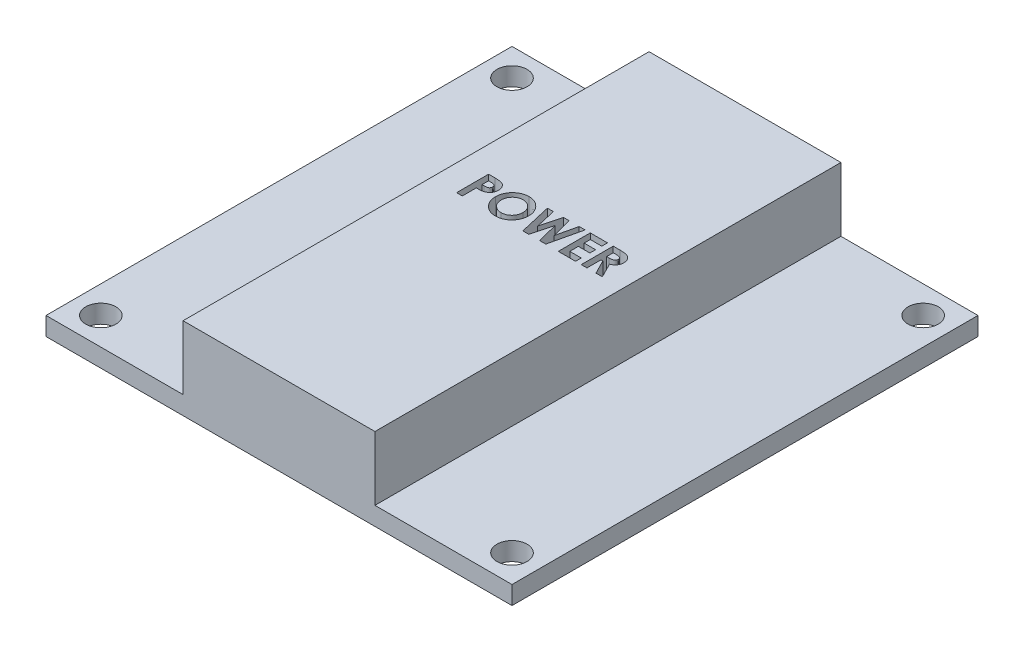
SolidWorks part; units mm, degrees
ref_plane "Front Plane" through (0, 0, 0) normal (0, 0, 1) x (1, 0, 0)
ref_plane "Top Plane" through (0, 0, 0) normal (0, 1, 0) x (1, 0, 0)
ref_plane "Right Plane" through (0, 0, 0) normal (1, 0, 0) x (0, 0, -1)
sketch "Sketch1" plane through (0, 0, 0) normal (0, 1, 0) x (1, 0, 0)
  line L1 (-17, 16.4148) -> (28, 16.4148) construction
  line L2 (-17, 16.4148) -> (-17, -28.5852) construction
  line L3 (-17, -28.5852) -> (28, -28.5852) construction
  line L4 (28, 16.4148) -> (28, -28.5852) construction
  line L5 (-20, 19.4148) -> (31, 19.4148)
  line L6 (-20, 19.4148) -> (-20, -31.5852)
  line L7 (-20, -31.5852) -> (31, -31.5852)
  line L8 (31, 19.4148) -> (31, -31.5852)
  circle A0 centre (-17, 16.4148) radius 1.65
  circle A1 centre (28, 16.4148) radius 1.65
  circle A2 centre (28, -28.5852) radius 1.65
  circle A3 centre (-17, -28.5852) radius 1.65
  dimension "D3" = 3.3
  dimension "D4" = 3
  dimension "D1" = 45
  dimension "D2" = 45
  dimension "D5" = 3
  dimension "D6" = 3
  dimension "D7" = 3
extrude "Boss-Extrude1" add sketch "Sketch1" along normal blind 9
sketch "Sketch2" plane through (0, 9, 0) normal (0, 1, 0) x (1, 0, 0)
  line L0 (-5, 4.4148) -> (-5, -16.5852)
  line L1 (-20, 19.4148) -> (-5, 19.4148)
  line L2 (-20, 19.4148) -> (-20, -31.5852)
  line L3 (-20, -31.5852) -> (-5, -31.5852)
  line L4 (31, 19.4148) -> (31, -31.5852)
  line L6 (16, 4.4148) -> (16, -16.5852)
  line L8 (-5, 4.4148) -> (-5, 19.4148)
  line L9 (16, 4.4148) -> (16, 19.4148)
  line L10 (16, -16.5852) -> (16, -31.5852)
  line L11 (-5, -16.5852) -> (-5, -31.5852)
  line L12 (16, 19.4148) -> (31, 19.4148)
  line L13 (-5, 4.4148) -> (16, 4.4148) construction
  line L14 (-5, -16.5852) -> (16, -16.5852) construction
  line L15 (-20, 19.4148) -> (31, 19.4148) construction
  line L16 (16, -31.5852) -> (31, -31.5852)
  line L17 (-20, -31.5852) -> (31, -31.5852) construction
  dimension "D1" = 15
extrude "Cut-Extrude1" cut sketch "Sketch2" against normal blind 7
sketch "Sketch3" plane through (0, 9, 0) normal (0, 1, 0) x (1, 0, 0)
  text T0 "<b>POWER</b>"
extrude "Cut-Extrude2" cut sketch "Sketch3" against normal blind 5
